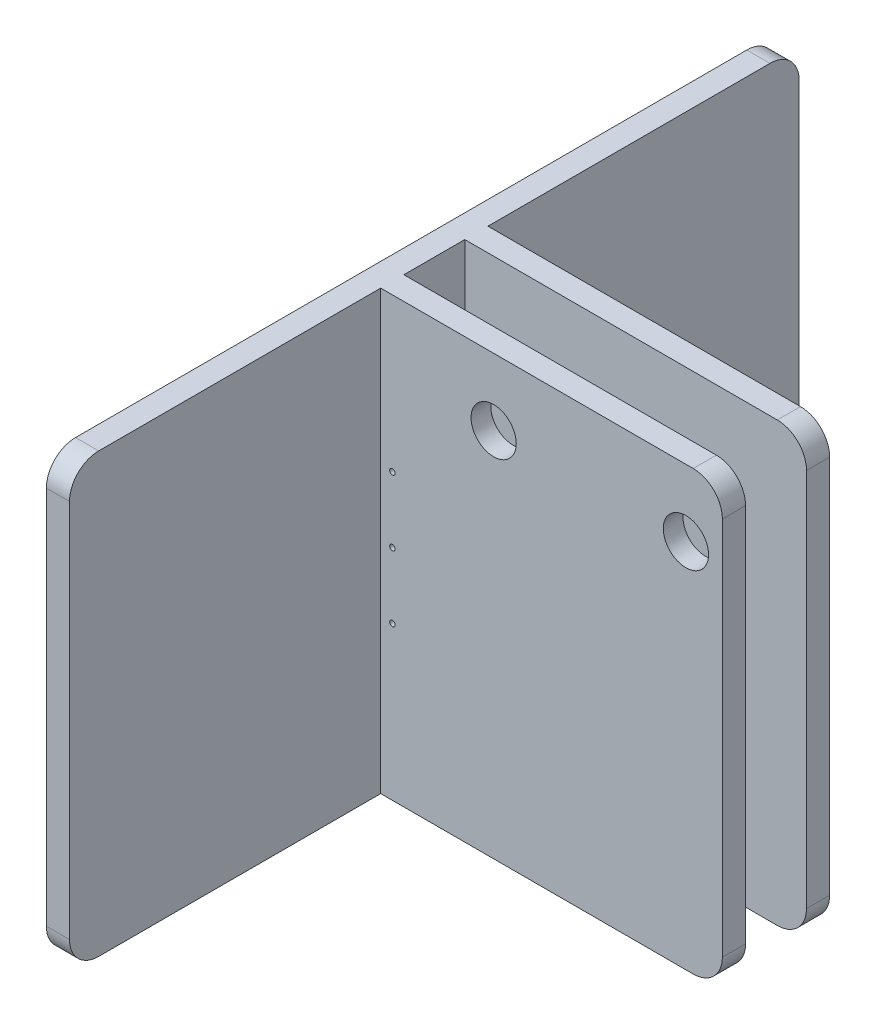
SolidWorks part; units mm, degrees
ref_plane "Front Plane" through (0, 0, 0) normal (0, 0, 1) x (1, 0, 0)
ref_plane "Top Plane" through (0, 0, 0) normal (0, 1, 0) x (1, 0, 0)
ref_plane "Right Plane" through (0, 0, 0) normal (1, 0, 0) x (0, 0, -1)
sketch "Sketch1" plane through (0, 0, 0) normal (0, 1, 0) x (1, 0, 0)
  line L0 (0, 7.35) -> (0, -7.35)
  line L5 (0, -7.35) -> (50, -7.35)
  line L6 (50, -7.35) -> (50, -4.175)
  line L17 (50, -4.175) -> (3.175, -4.175)
  line L18 (3.175, -4.175) -> (3.175, 4.175)
  line L19 (0, 0) -> (39.6882, 0) construction
  line L20 (50, 4.175) -> (3.175, 4.175)
  line L21 (50, 7.35) -> (50, 4.175)
  line L22 (0, 7.35) -> (50, 7.35)
  point P9 (3.175, 0)
  dimension "D1" = 14.7
  dimension "D2" = 3.175
  dimension "D3" = 3.175
  dimension "D4" = 50
extrude "Boss-Extrude1" add sketch "Sketch1" along normal blind 60
sketch "Sketch3" plane through (0, 0, 7.35) normal (0, 0, 1) x (1, 0, 0)
  line L1 (50, 60) -> (50, 0) construction
  line L2 (0, 60) -> (50, 60) construction
  circle A0 centre (45, 50.82) radius 3.1
  circle A1 centre (18.65, 50.82) radius 3.1
  point P8 (0, 0)
  dimension "D1" = 6.2
  dimension "D2" = 9.18
  dimension "D3" = 5
  dimension "D4" = 26.35
extrude "Cut-Extrude1" cut sketch "Sketch3" against normal blind 2.7
sketch "Sketch4" plane through (0, 0, -7.35) normal (0, 0, -1) x (-1, 0, 0)
  line L1 (-50, 60) -> (-50, 0) construction
  line L2 (0, 60) -> (-50, 60) construction
  circle A0 centre (-45, 50.82) radius 3.1
  circle A1 centre (-18.65, 50.82) radius 3.1
  point P4 (0, 0)
  dimension "D4" = 6.2
  dimension "D1" = 9.18
  dimension "D2" = 5
  dimension "D3" = 26.35
extrude "Cut-Extrude2" cut sketch "Sketch4" against normal blind 2.7
fillet "Fillet1" radius 4 4 edges at (50, 60, 5.7625) (50, 60, -5.7625) (50, 0, -5.7625) (50, 0, 5.7625)
sketch "Sketch5" plane through (0, 0, 7.35) normal (0, 0, 1) x (1, 0, 0)
  line L0 (0, 30) -> (50, 30) construction
  line L1 (0, 60) -> (0, 0) construction
  line L2 (50, 56) -> (50, 4) construction
  circle A0 centre (4.7792, 21) radius 0.375
  circle A1 centre (4.7792, 39) radius 0.375
  circle A2 centre (4.7792, 30) radius 0.375
  point P10 (0, 0)
  dimension "D3" = 0.75
  dimension "D1" = 9
  dimension "D2" = 9
extrude "Cut-Extrude3" cut sketch "Sketch5" against normal up to surface (14.7 mm away) up to face at (41.9, 50.82, -7.35)
sketch "Sketch6" plane through (0, 0, 7.35) normal (0, 0, 1) x (1, 0, 0)
  line L0 (0, 0) -> (46, 0) construction
  line L1 (0, 60) -> (3.175, 60)
  line L2 (0, 60) -> (0, 0)
  line L3 (0, 0) -> (3.175, 0)
  line L4 (3.175, 60) -> (3.175, 0)
  dimension "D1" = 3.175
extrude "Boss-Extrude2" add sketch "Sketch6" along normal blind 42.65
sketch "Sketch7" plane through (0, 0, -7.35) normal (0, 0, -1) x (-1, 0, 0)
  line L0 (-46, 60) -> (0, 60) construction
  line L1 (0, 0) -> (-3.175, 0)
  line L2 (0, 0) -> (0, 60)
  line L3 (0, 60) -> (-3.175, 60)
  line L4 (-3.175, 0) -> (-3.175, 60)
  dimension "D1" = 3.175
extrude "Boss-Extrude3" add sketch "Sketch7" along normal blind 42.65
fillet "Fillet2" radius 4 4 edges at (1.5875, 0, -50) (1.5875, 60, -50) (1.5875, 0, 50) (1.5875, 60, 50)
equation "\"D2@Sketch5\"=\"D1@Sketch5\""
